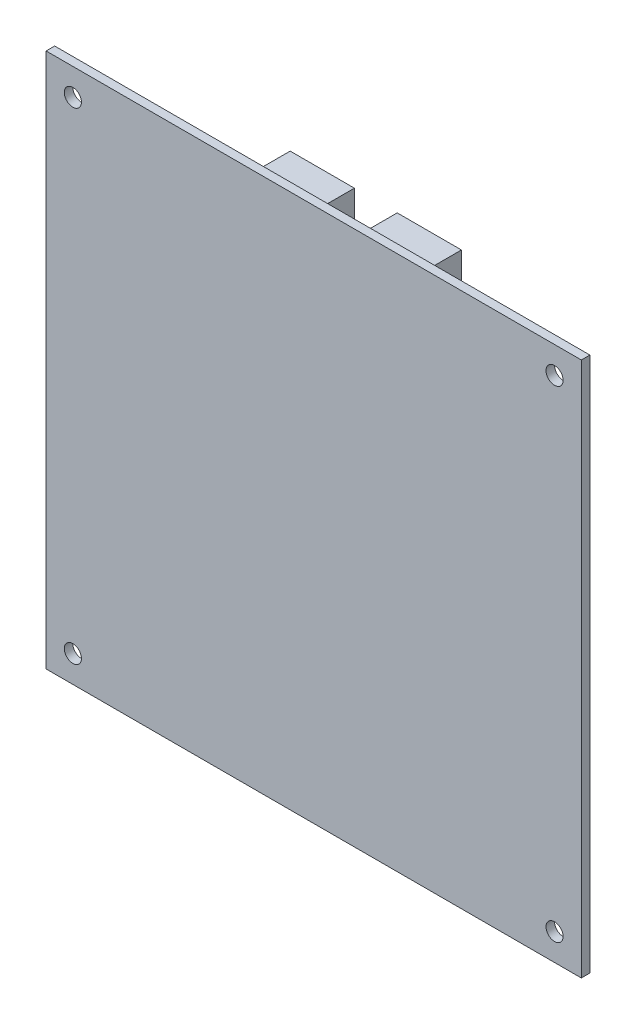
SolidWorks part; units mm, degrees
ref_plane "前视基准面" through (0, 0, 0) normal (0, 0, 1) x (1, 0, 0)
ref_plane "上视基准面" through (0, 0, 0) normal (0, 1, 0) x (1, 0, 0)
ref_plane "右视基准面" through (0, 0, 0) normal (1, 0, 0) x (0, 0, -1)
other "Configuration Table"
sketch "草图1" plane through (0, 0, 0) normal (0, 0, 1) x (1, 0, 0)
  line L0 (0, 0) -> (100, 0)
  line L1 (100, 0) -> (100, 100)
  line L2 (100, 100) -> (0, 100)
  line L3 (0, 100) -> (0, 0)
  circle A0 centre (5, 5) radius 1.6
  circle A1 centre (95, 5) radius 1.6
  circle A2 centre (5, 95) radius 1.6
  circle A3 centre (95, 95) radius 1.6
extrude "100x100_板厚1p6" add sketch "草图1" along normal blind 1.6
sketch "草图2" plane through (0, 0, 0) normal (0, 0, 1) x (1, 0, 0)
  line L0 (26, 20) -> (30, 20)
  line L1 (30, 20) -> (30, 78)
  line L2 (30, 78) -> (26, 78)
  line L3 (26, 78) -> (26, 20)
extrude "排母左" add sketch "草图2" along normal blind 8 from offset 8
sketch "草图3" plane through (0, 0, 0) normal (0, 0, 1) x (1, 0, 0)
  line L0 (70, 20) -> (74, 20)
  line L1 (74, 20) -> (74, 78)
  line L2 (74, 78) -> (70, 78)
  line L3 (70, 78) -> (70, 20)
extrude "排母右" add sketch "草图3" along normal blind 8 from offset 8
sketch "草图4" plane through (0, 0, 0) normal (0, 0, 1) x (1, 0, 0)
  line L0 (34, 26) -> (66, 26)
  line L1 (66, 26) -> (66, 73)
  line L2 (66, 73) -> (34, 73)
  line L3 (34, 73) -> (34, 26)
extrude "控制器占位" add sketch "草图4" along normal blind 16 from offset 16
sketch "草图5" plane through (0, 0, 0) normal (0, 0, 1) x (1, 0, 0)
  line L0 (40, 3) -> (60, 3)
  line L1 (60, 3) -> (60, 13)
  line L2 (60, 13) -> (40, 13)
  line L3 (40, 13) -> (40, 3)
extrude "电源端子示意" add sketch "草图5" along normal blind 12 from offset 12
sketch "草图6" plane through (0, 0, 0) normal (0, 0, 1) x (1, 0, 0)
  line L0 (34, 85) -> (46, 85)
  line L1 (46, 85) -> (46, 95)
  line L2 (46, 95) -> (34, 95)
  line L3 (34, 95) -> (34, 85)
extrude "接口示意左" add sketch "草图6" along normal blind 10 from offset 10
sketch "草图7" plane through (0, 0, 0) normal (0, 0, 1) x (1, 0, 0)
  line L0 (54, 85) -> (66, 85)
  line L1 (66, 85) -> (66, 95)
  line L2 (66, 95) -> (54, 95)
  line L3 (54, 95) -> (54, 85)
extrude "接口示意右" add sketch "草图7" along normal blind 10 from offset 10
